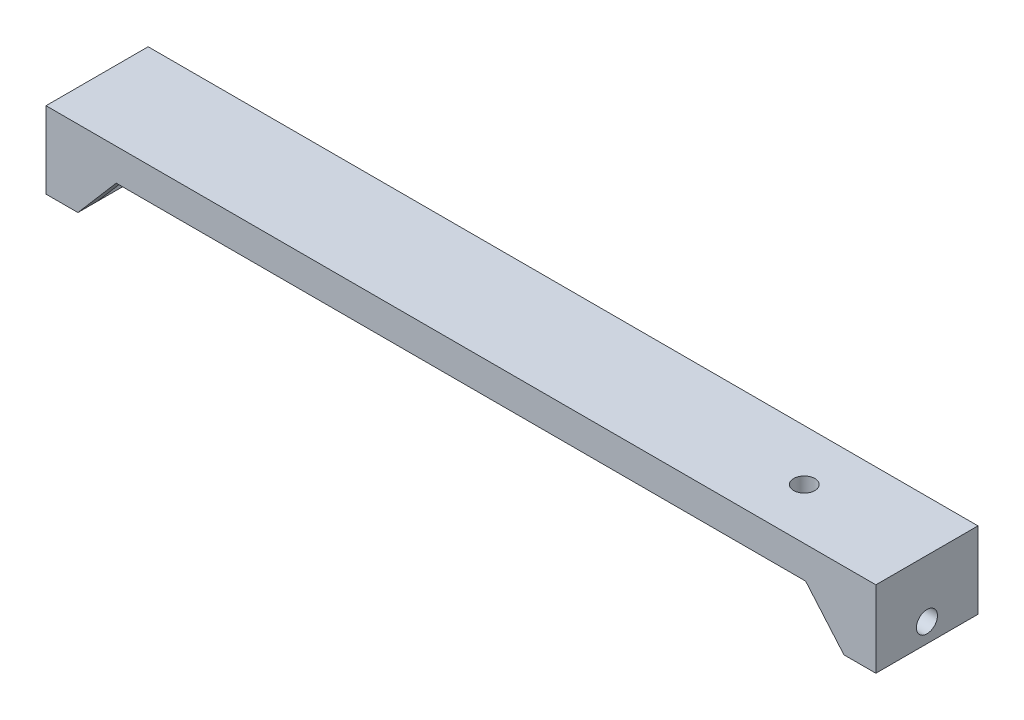
SolidWorks part; units mm, degrees
ref_plane "前视基准面" through (0, 0, 0) normal (0, 0, 1) x (1, 0, 0)
ref_plane "上视基准面" through (0, 0, 0) normal (0, 1, 0) x (1, 0, 0)
ref_plane "右视基准面" through (0, 0, 0) normal (1, 0, 0) x (0, 0, -1)
sketch "草图1" plane through (0, 0, 0) normal (0, 0, 1) x (1, 0, 0)
  line L0 (-65, 0) -> (65, 0)
  line L1 (65, 0) -> (65, -12)
  line L2 (65, -12) -> (60, -12)
  line L3 (60, -12) -> (60, -5)
  line L4 (60, -5) -> (-60, -5)
  line L5 (-60, -5) -> (-60, -12)
  line L6 (-60, -12) -> (-65, -12)
  line L7 (-65, -12) -> (-65, 0)
  line L8 (0, -7.4248) -> (0, 9.2484) construction
  dimension "D1" = 5
  dimension "D2" = 5
  dimension "D3" = 130
  dimension "D4" = 12
  dimension "D5" = 12
extrude "凸台-拉伸2" add sketch "草图1" along normal blind 16
sketch "草图3" plane through (-60, 0, 0) normal (1, 0, 0) x (0, 0, -1)
  line L1 (-16, -12) -> (0, -12) construction
  line L2 (0, 0) -> (0, -12) construction
  circle A0 centre (-8, -9) radius 1.65
  dimension "D2" = 3.3
  dimension "D1" = 3
  dimension "D3" = 8
extrude "切除-拉伸1" cut sketch "草图3" against normal through all both and the other way through all
sketch "草图4" plane through (0, 0, 0) normal (0, 0, -1) x (-1, 0, 0)
  line L0 (54, -5) -> (60, -12)
  line L1 (60, -5) -> (-60, -5) construction
  line L2 (54, -5) -> (60, -5)
  line L4 (60, -5) -> (60, -12)
  dimension "D1" = 6
extrude "凸台-拉伸3" add sketch "草图4" against normal blind 3
sketch "草图5" plane through (0, -5, 0) normal (0, -1, 0) x (1, 0, 0)
  line L0 (60, 8) -> (-60, 8) construction
  line L1 (60, 16) -> (60, 0) construction
  line L2 (-60, 16) -> (-60, 3) construction
ref_plane "基准面3" through (0, 0, 8) normal (0, 0, 1) x (1, 0, 0)
mirror "镜向1" about plane through (0, 0, 8) normal (0, 0, 1) of "凸台-拉伸3"
sketch "草图6" plane through (0, 0, 0) normal (0, 1, 0) x (1, 0, 0)
  line L0 (0, -16) -> (0, 0) construction
  line L1 (65, -16) -> (-65, -16) construction
mirror "镜向2" about plane through (0, 0, 0) normal (1, 0, 0) of "镜向1", "凸台-拉伸3"
sketch "草图7" plane through (0, 0, 0) normal (0, 1, 0) x (1, 0, 0)
  line L0 (65, -16) -> (65, 0) construction
  line L1 (65, -16) -> (-65, -16) construction
  circle A0 centre (45.79, -8) radius 1.65
  dimension "D1" = 3.3
  dimension "D2" = 19.21
  dimension "D3" = 8
extrude "切除-拉伸2" cut sketch "草图7" against normal blind 10
